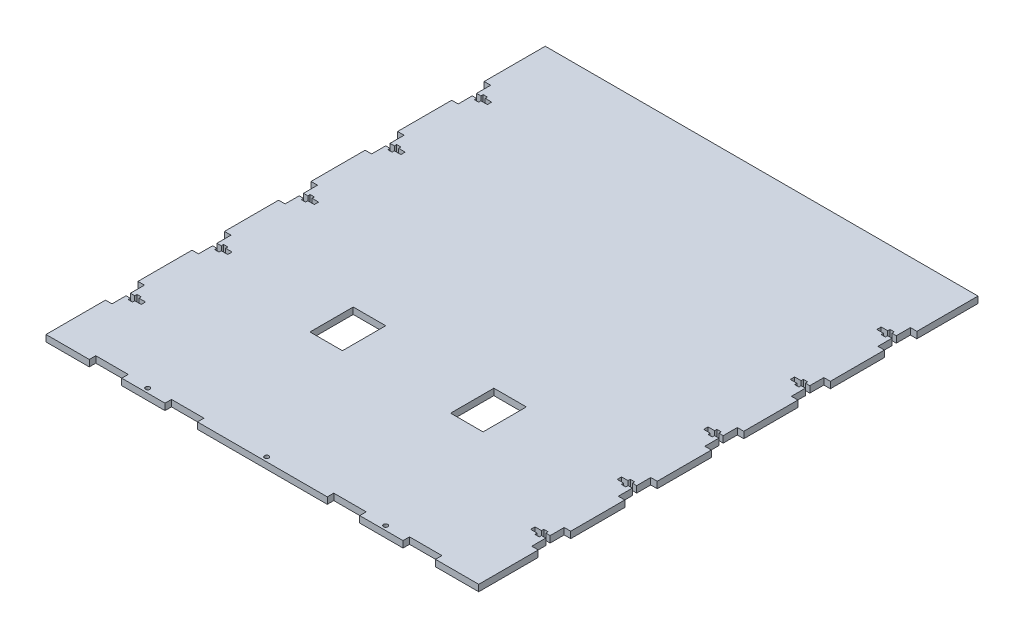
SolidWorks part; units mm, degrees
ref_plane "Front" through (0, 0, 0) normal (0, 0, 1) x (1, 0, 0)
ref_plane "Top" through (0, 0, 0) normal (0, 1, 0) x (1, 0, 0)
ref_plane "Right" through (0, 0, 0) normal (1, 0, 0) x (0, 0, -1)
sketch "草图1" plane through (0, 0, 0) normal (0, 1, 0) x (1, 0, 0)
  line L1 (0, 0) -> (200, 0)
  line L2 (0, 0) -> (0, 230.75)
  line L3 (0, 230.75) -> (200, 230.75)
  line L4 (200, 0) -> (200, 230.75)
  dimension "D1" = 230.75
  dimension "D2" = 200
extrude "凸台-拉伸1" add sketch "草图1" along normal blind 3
sketch "草图2" plane through (0, 3, 0) normal (0, 1, 0) x (1, 0, 0)
  line L0 (0, 230.75) -> (0, 0) construction
  line L1 (0, 202.5) -> (3, 202.5)
  line L2 (0, 202.5) -> (0, 187.5)
  line L3 (0, 187.5) -> (3, 187.5)
  line L4 (3, 202.5) -> (3, 187.5)
  line L5 (200, 230.75) -> (0, 230.75) construction
  line L6 (200, 0) -> (200, 230.75) construction
  line L7 (200, 202.5) -> (197, 202.5)
  line L8 (200, 202.5) -> (200, 187.5)
  line L9 (200, 187.5) -> (197, 187.5)
  line L10 (197, 202.5) -> (197, 187.5)
  dimension "D3" = 28.25
  dimension "D1" = 15
  dimension "D2" = 3
  dimension "D4" = 3
  dimension "D5" = 15
  dimension "D6" = 28.25
extrude "切除-拉伸1" cut sketch "草图2" against normal through all
pattern_linear "阵列(线性)1" count 5 spacing 40 along (0, 0, 1) of "切除-拉伸1"
sketch "草图3" plane through (0, 3, 0) normal (0, 1, 0) x (1, 0, 0)
  line L0 (0, 0) -> (200, 0) construction
  line L1 (20, 0) -> (35, 0)
  line L2 (20, 0) -> (20, 3)
  line L3 (20, 3) -> (35, 3)
  line L4 (35, 0) -> (35, 3)
  line L6 (55, 0) -> (70, 0)
  line L7 (55, 0) -> (55, 3)
  line L8 (55, 3) -> (70, 3)
  line L9 (70, 0) -> (70, 3)
  line L10 (130, 0) -> (145, 0)
  line L11 (130, 0) -> (130, 3)
  line L12 (130, 3) -> (145, 3)
  line L13 (145, 0) -> (145, 3)
  line L14 (165, 0) -> (180, 0)
  line L15 (165, 0) -> (165, 3)
  line L16 (165, 3) -> (180, 3)
  line L17 (180, 0) -> (180, 3)
  point P10 (100, 0)
  point P19 (145, 1.5)
  dimension "D1" = 15
  dimension "D2" = 3
  dimension "D3" = 15
  dimension "D4" = 3
  dimension "D5" = 30
  dimension "D6" = 20
  dimension "D7" = 15
  dimension "D8" = 3
  dimension "D9" = 30
  dimension "D10" = 15
  dimension "D11" = 3
  dimension "D12" = 20
extrude "切除-拉伸2" cut sketch "草图3" against normal through all
sketch "草图4" plane through (0, 3, 0) normal (0, 1, 0) x (1, 0, 0)
  line L0 (70, 0) -> (130, 0) construction
  line L1 (35, 0) -> (55, 0) construction
  line L2 (145, 0) -> (165, 0) construction
  circle A0 centre (100, 2) radius 1
  circle A1 centre (45, 2) radius 1
  circle A2 centre (155, 2) radius 1
  point P8 (45, 0)
  point P13 (155, 0)
  dimension "D1" = 2
  dimension "D2" = 0
  dimension "D3" = 0
extrude "切除-拉伸3" cut sketch "草图4" against normal through all
sketch "草图5" plane through (0, 3, 0) normal (0, 1, 0) x (1, 0, 0)
  line L0 (3, 187.5) -> (3, 202.5) construction
  line L1 (5, 197.05) -> (7, 197.05)
  line L2 (5, 197.05) -> (5, 196)
  line L3 (5, 192.95) -> (7, 192.95)
  line L4 (7, 197.05) -> (7, 196)
  line L5 (3, 196) -> (5, 196)
  line L6 (3, 196) -> (3, 194)
  line L7 (3, 194) -> (5, 194)
  line L8 (10, 196) -> (10, 194)
  line L9 (5, 194) -> (5, 192.95)
  line L10 (7, 196) -> (10, 196)
  line L11 (7, 194) -> (7, 192.95)
  line L12 (7, 194) -> (10, 194)
  point P8 (3, 195)
  point P11 (3, 195)
  dimension "D1" = 4.1
  dimension "D2" = 2
  dimension "D3" = 1.05
  dimension "D4" = 2
  dimension "D5" = 2
  dimension "D6" = 7
  dimension "D7" = 0
  dimension "D8" = 0
extrude "切除-拉伸4" cut sketch "草图5" against normal through all
pattern_linear "阵列(线性)2" count 5 spacing 40 along (0, 0, 1) of "切除-拉伸4"
ref_plane "基准面1" through (100, 0, 0) normal (-1, 0, 0) x (0, 0, 1)
mirror "镜向1" about plane through (100, 0, 0) normal (-1, 0, 0) of "阵列(线性)2", "切除-拉伸4"
sketch "草图6" plane through (0, 3, 0) normal (0, 1, 0) x (1, 0, 0)
  line L0 (70, 0) -> (130, 0) construction
  line L1 (60, 82) -> (75, 82)
  line L2 (60, 82) -> (60, 62)
  line L3 (60, 62) -> (75, 62)
  line L4 (75, 82) -> (75, 62)
  line L5 (125, 82) -> (140, 82)
  line L6 (125, 82) -> (125, 62)
  line L7 (125, 62) -> (140, 62)
  line L8 (140, 82) -> (140, 62)
  line L9 (0, 67.5) -> (0, 42.5) construction
  line L10 (145, 0) -> (165, 0) construction
  line L11 (200, 82.5) -> (200, 107.5) construction
  dimension "D1" = 15
  dimension "D2" = 15
  dimension "D3" = 20
  dimension "D4" = 20
  dimension "D5" = 62
  dimension "D6" = 60
  dimension "D7" = 62
  dimension "D8" = 60
extrude "切除-拉伸5" cut sketch "草图6" against normal through all
